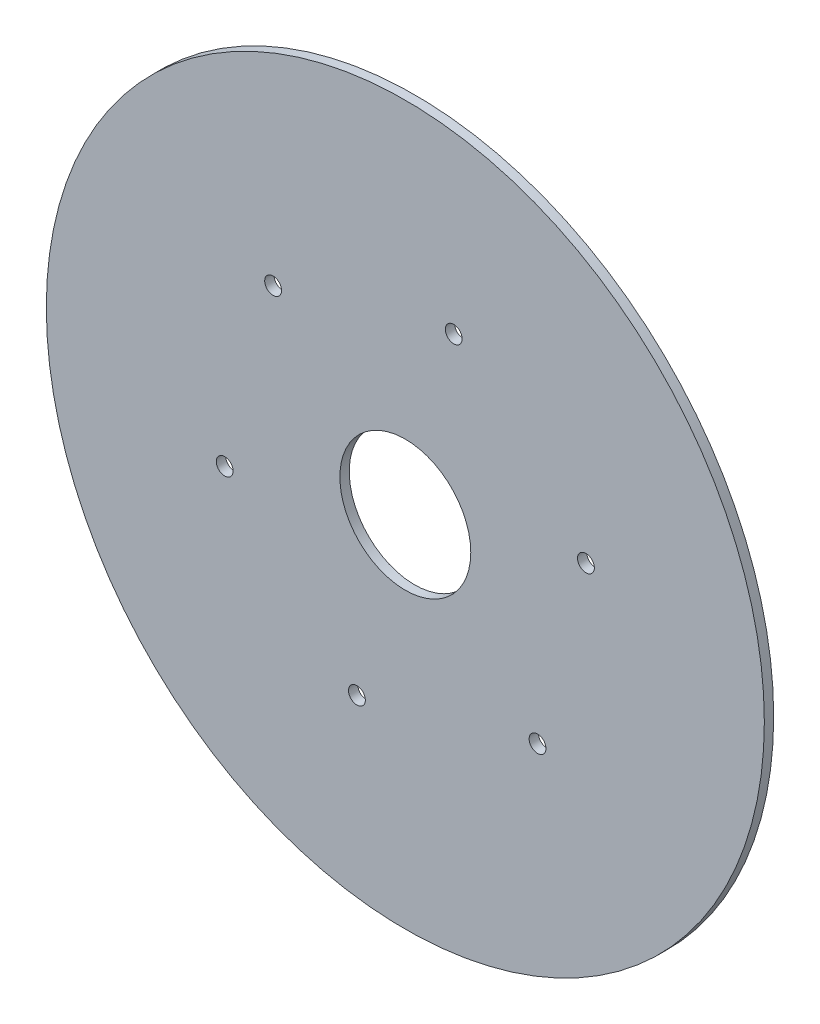
SolidWorks part; units mm, degrees
ref_plane "Спереди" through (0, 0, 0) normal (0, 0, 1) x (1, 0, 0)
ref_plane "Сверху" through (0, 0, 0) normal (0, 1, 0) x (1, 0, 0)
ref_plane "Справа" through (0, 0, 0) normal (1, 0, 0) x (0, 0, -1)
sketch "Эскиз1" plane through (0, 0, 0) normal (0, 0, 1) x (1, 0, 0)
  circle A0 centre (0, 0) radius 96
  circle A1 centre (0, 0) radius 17.5
extrude "Front_cover_reference" add sketch "Эскиз1" along normal blind 2.5 from offset 58.5
sketch "Эскиз2" plane through (0, 0, 0) normal (0, 0, 1) x (1, 0, 0)
  circle A0 centre (48.2963, 12.941) radius 2.25
  circle A1 centre (12.941, 48.2963) radius 2.25
  circle A2 centre (-35.3553, 35.3553) radius 2.25
  circle A3 centre (-48.2963, -12.941) radius 2.25
  circle A4 centre (-12.941, -48.2963) radius 2.25
  circle A5 centre (35.3553, -35.3553) radius 2.25
extrude "Through_holes" cut sketch "Эскиз2" against normal mid plane 200
